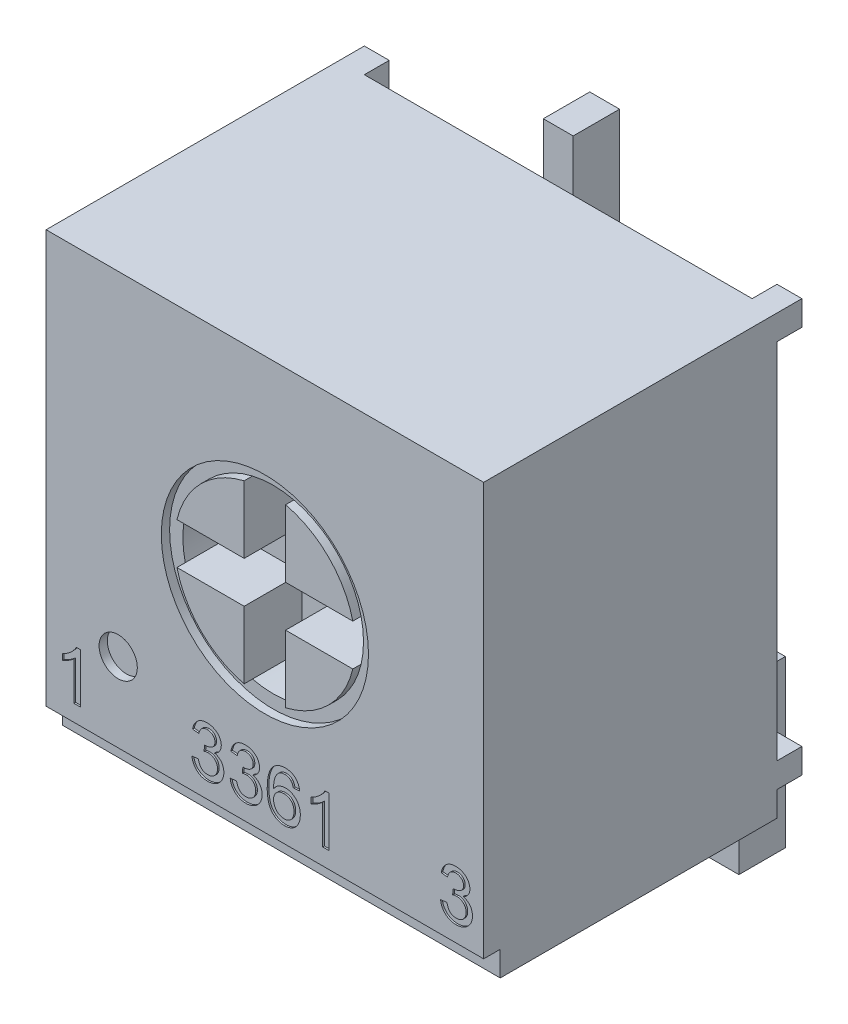
SolidWorks part; units mm, degrees
material "PC High Viscosity"
ref_plane "Plane1" through (0, 0, 0) normal (0, 0, 1) x (1, 0, 0)
ref_plane "Plane2" through (0, 0, 0) normal (0, 1, 0) x (1, 0, 0)
ref_plane "Plane3" through (0, 0, 0) normal (1, 0, 0) x (0, 0, -1)
sketch "Sketch1" plane through (0, 0, 0) normal (0, 0, 1) x (1, 0, 0)
  line L1 (0, 0) -> (6.7056, 0)
  line L2 (0, 0) -> (0, 6.7056)
  line L3 (0, 6.7056) -> (6.7056, 6.7056)
  line L4 (6.7056, 0) -> (6.7056, 6.7056)
  dimension "D1" = 6.7056
  dimension "D2" = 6.7056
extrude "Extrude1" add sketch "Sketch1" along normal blind 4.4958
sketch "Sketch2" plane through (0, 0, 4.4958) normal (0, 0, 1) x (1, 0, 0)
  line L0 (6.7056, 0) -> (6.7056, 6.7056) construction
  line L1 (0, 0) -> (6.7056, 0)
  line L2 (0, 0) -> (0, 0.381)
  line L3 (0, 0.381) -> (6.7056, 0.381)
  line L4 (6.7056, 0) -> (6.7056, 0.381)
  dimension "D1" = 0.381
extrude "Cut-Extrude1" cut sketch "Sketch2" against normal blind 0.254
sketch "Sketch3" plane through (0, 0, 0) normal (0, -1, 0) x (1, 0, 0)
  line L0 (0, 0) -> (6.7056, 0) construction
  line L1 (1.016, 0) -> (2.286, 0)
  line L2 (1.016, 0) -> (1.016, 3.81)
  line L3 (1.016, 3.81) -> (2.286, 3.81)
  line L4 (2.286, 0) -> (2.286, 3.81)
  line L5 (0, 4.2418) -> (0, 0) construction
  line L6 (5.6896, 0) -> (4.4196, 0)
  line L7 (5.6896, 0) -> (5.6896, 3.81)
  line L8 (5.6896, 3.81) -> (4.4196, 3.81)
  line L9 (4.4196, 0) -> (4.4196, 3.81)
  line L10 (6.7056, 4.2418) -> (6.7056, 0) construction
  dimension "D1" = 3.81
  dimension "D2" = 1.016
  dimension "D3" = 1.016
  dimension "D4" = 1.27
  dimension "D5" = 1.27
extrude "Extrude2" add sketch "Sketch3" along normal blind 0.3302
sketch "Sketch4" plane through (6.7056, 0, 0) normal (1, 0, 0) x (0, 0, -1)
  line L0 (0, 0) -> (0, 6.7056) construction
  line L1 (0, 6.7056) -> (0.381, 6.7056)
  line L2 (0, 6.7056) -> (0, 6.3246)
  line L3 (0, 6.3246) -> (0.381, 6.3246)
  line L4 (0.381, 6.7056) -> (0.381, 6.3246)
  line L5 (0, 0.762) -> (0.381, 0.762)
  line L6 (0, 0.762) -> (0, 0.381)
  line L7 (0, 0.381) -> (0.381, 0.381)
  line L8 (0.381, 0.762) -> (0.381, 0.381)
  line L9 (-4.2418, 0) -> (0, 0) construction
  dimension "D1" = 0.381
  dimension "D2" = 0.381
  dimension "D3" = 0.381
  dimension "D4" = 0.381
extrude "Extrude3" add sketch "Sketch4" against normal blind 0.381
ref_plane "Plane4" through (3.3528, 0, 0) normal (1, 0, 0) x (0, 0, -1)
mirror "Mirror1" about plane through (3.3528, 0, 0) normal (1, 0, 0) of "Extrude3"
ref_plane "Plane5" through (0, 0, -0.7112) normal (0, 0, 1) x (1, 0, 0)
sketch "Sketch5" plane through (0, 0, -0.7112) normal (0, 0, 1) x (1, 0, 0)
  line L0 (3.3528, 4.953) -> (3.3528, 6.7056) construction
  line L1 (3.1242, 4.953) -> (3.5814, 4.953)
  line L2 (3.1242, 4.953) -> (3.1242, 7.493)
  line L3 (3.1242, 7.493) -> (3.5814, 7.493)
  line L4 (3.5814, 4.953) -> (3.5814, 7.493)
  line L5 (6.3246, 6.7056) -> (0.381, 6.7056) construction
  line L6 (0.8128, 1.4986) -> (0.8128, 2.3719) construction
  line L7 (0.5842, -1.0414) -> (1.0414, -1.0414)
  line L8 (0.5842, -1.0414) -> (0.5842, 1.4986)
  line L9 (0.5842, 1.4986) -> (1.0414, 1.4986)
  line L10 (1.0414, -1.0414) -> (1.0414, 1.4986)
  line L11 (5.6642, -1.0414) -> (5.6642, 1.4986)
  line L12 (6.1214, 1.4986) -> (5.6642, 1.4986)
  line L13 (6.1214, -1.0414) -> (6.1214, 1.4986)
  line L14 (6.1214, -1.0414) -> (5.6642, -1.0414)
  dimension "D1" = 0.7874
  dimension "D2" = 2.54
  dimension "D3" = 0.4572
  dimension "D4" = 0.4572
  dimension "D5" = 8.5344
  dimension "D6" = 2.54
  dimension "D7" = 2.54
extrude "Extrude4" add sketch "Sketch5" along normal up to surface (0.7112 mm away) up to face at (3.3819, 1.6187, 0)
sketch "Sketch6" plane through (0, 0, 4.4958) normal (0, 0, 1) x (1, 0, 0)
  line L0 (0, 0.381) -> (6.7056, 6.7056) construction
  line L1 (2.286, -0.3302) -> (1.016, -0.3302) construction
  circle A0 centre (3.3528, 3.5433) radius 1.3843
  circle A1 centre (3.3528, 3.5433) radius 1.5875
  dimension "D1" = 2.7686
  dimension "D2" = 3.175
  dimension "D3" = 3.8735
extrude "Cut-Extrude2" cut sketch "Sketch6" against normal blind 0.127
sketch "Sketch7" plane through (0, 0, 4.4958) normal (0, 0, 1) x (1, 0, 0)
  line L0 (3.0353, 4.8907) -> (3.0353, 3.8608)
  line L1 (3.0353, 3.8608) -> (2.0054, 3.8608)
  line L2 (2.0054, 3.2258) -> (3.0353, 3.2258)
  line L3 (3.0353, 3.2258) -> (3.0353, 2.1959)
  line L5 (3.6703, 2.1959) -> (3.6703, 3.2258)
  line L6 (3.6703, 3.2258) -> (4.7002, 3.2258)
  line L8 (4.7002, 3.8608) -> (3.6703, 3.8608)
  line L9 (3.6703, 3.8608) -> (3.6703, 4.8907)
  circle A0 centre (3.3528, 3.5433) radius 1.3843 construction
  arc A1 (3.6703, 4.8907) -> (3.0353, 4.8907) centre (3.3528, 3.5433) ccw
  arc A2 (2.0054, 3.8608) -> (2.0054, 3.2258) centre (3.3528, 3.5433) ccw
  arc A3 (3.0353, 2.1959) -> (3.6703, 2.1959) centre (3.3528, 3.5433) ccw
  arc A4 (4.7002, 3.2258) -> (4.7002, 3.8608) centre (3.3528, 3.5433) ccw
  dimension "D1" = 0.635
  dimension "D2" = 0.3175
  dimension "D3" = 0.635
  dimension "D4" = 0.3175
extrude "Cut-Extrude3" cut sketch "Sketch7" against normal blind 0.889
sketch "Sketch8" plane through (0, 0, 4.4958) normal (0, 0, 1) x (1, 0, 0)
  circle A0 centre (1.1046, 1.5911) radius 0.293
extrude "Cut-Extrude4" cut sketch "Sketch8" against normal blind 0.127
sketch "Sketch9" plane through (0, 0, 4.4958) normal (0, 0, 1) x (1, 0, 0)
  text T0 "1     3361     3" font "Arial" height 0.762
extrude "Cut-Extrude5" cut sketch "Sketch9" against normal blind 0.0254
